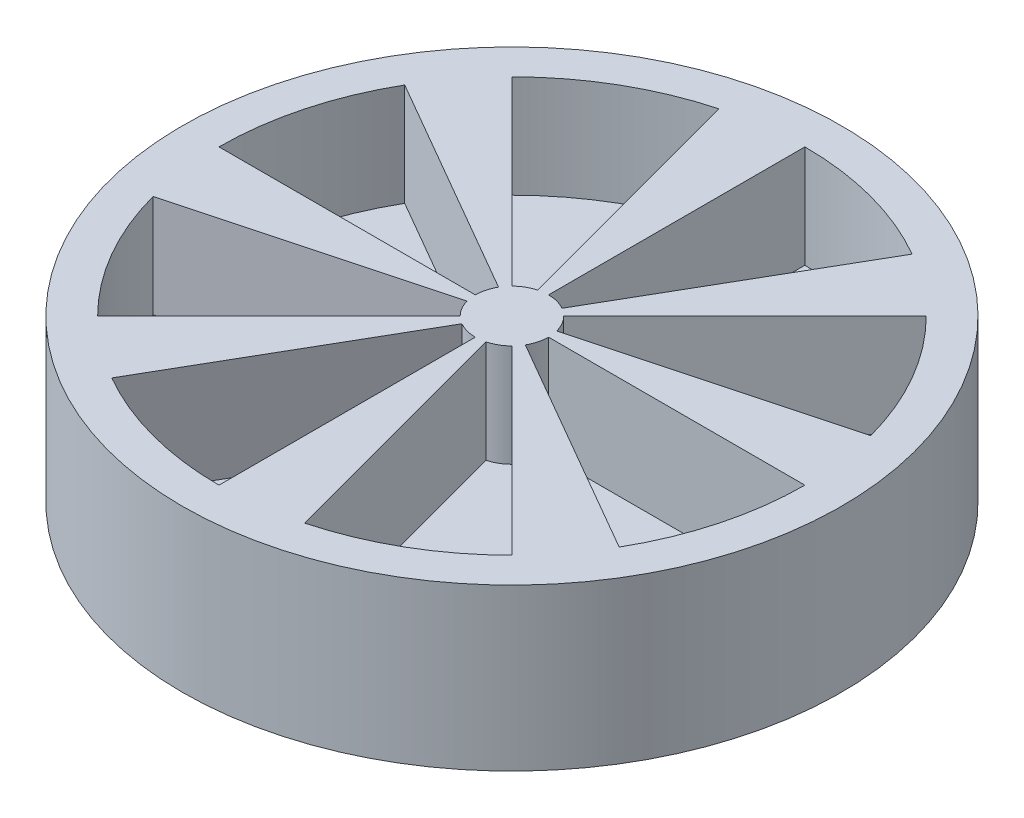
SolidWorks part; units mm, degrees
ref_plane "Front Plane" through (0, 0, 0) normal (0, 0, 1) x (1, 0, 0)
ref_plane "Top Plane" through (0, 0, 0) normal (0, 1, 0) x (1, 0, 0)
ref_plane "Right Plane" through (0, 0, 0) normal (1, 0, 0) x (0, 0, -1)
sketch "Sketch1" plane through (0, 0, 0) normal (0, 1, 0) x (1, 0, 0)
  circle A0 centre (0, 0) radius 22.5
  dimension "D1" = 45
extrude "Main Extrude for Plastic Mechansim Part" add sketch "Sketch1" along normal blind 11
sketch "Sketch2" plane through (0, 11, 0) normal (0, 1, 0) x (1, 0, 0)
  line L0 (0, 20) -> (0, 2.5)
  line L1 (-20, 0) -> (-2.5, 0)
  line L2 (-14.1421, -14.1421) -> (-1.7678, -1.7678)
  line L3 (-14.1421, 14.1421) -> (-1.7678, 1.7678)
  line L4 (-17.3205, 10) -> (-2.1651, 1.25)
  line L5 (-19.3185, 5.1764) -> (-2.4148, 0.647) construction
  line L6 (-19.3185, -5.1764) -> (-2.4148, -0.647)
  line L7 (-17.3205, -10) -> (-2.1651, -1.25) construction
  line L8 (10, 17.3205) -> (1.25, 2.1651)
  line L9 (5.1764, 19.3185) -> (0.647, 2.4148) construction
  line L10 (-5.1764, 19.3185) -> (-0.647, 2.4148)
  line L11 (-10, 17.3205) -> (-1.25, 2.1651) construction
  line L12 (0, -2.5) -> (0, -20)
  line L13 (-0.647, -2.4148) -> (-5.1764, -19.3185) construction
  line L14 (-1.25, -2.1651) -> (-10, -17.3205)
  line L15 (1.7678, 1.7678) -> (14.1421, 14.1421)
  line L16 (2.1651, 1.25) -> (17.3205, 10) construction
  line L17 (2.4148, 0.647) -> (19.3185, 5.1764)
  line L18 (2.5, 0) -> (20, 0)
  line L19 (2.4148, -0.647) -> (19.3185, -5.1764) construction
  line L20 (2.1651, -1.25) -> (17.3205, -10)
  line L21 (1.7678, -1.7678) -> (14.1421, -14.1421)
  line L22 (1.25, -2.1651) -> (10, -17.3205) construction
  line L23 (0.647, -2.4148) -> (5.1764, -19.3185)
  arc A0 (-5.1764, 19.3185) -> (-14.1421, 14.1421) centre (0, 0) ccw
  arc A1 (10, 17.3205) -> (0, 20) centre (0, 0) ccw
  arc A2 (19.3185, 5.1764) -> (14.1421, 14.1421) centre (0, 0) ccw
  arc A3 (17.3205, -10) -> (20, 0) centre (0, 0) ccw
  arc A4 (5.1764, -19.3185) -> (14.1421, -14.1421) centre (0, 0) ccw
  arc A5 (-10, -17.3205) -> (0, -20) centre (0, 0) ccw
  arc A6 (-19.3185, -5.1764) -> (-14.1421, -14.1421) centre (0, 0) ccw
  arc A7 (-17.3205, 10) -> (-20, 0) centre (0, 0) ccw
  arc A8 (-0.647, 2.4148) -> (-1.7678, 1.7678) centre (0, 0) ccw
  arc A9 (-2.1651, 1.25) -> (-2.5, 0) centre (0, 0) ccw
  arc A10 (-2.4148, -0.647) -> (-1.7678, -1.7678) centre (0, 0) ccw
  arc A11 (-1.25, -2.1651) -> (0, -2.5) centre (0, 0) ccw
  arc A12 (0.647, -2.4148) -> (1.7678, -1.7678) centre (0, 0) ccw
  arc A13 (2.1651, -1.25) -> (2.5, 0) centre (0, 0) ccw
  arc A14 (2.4148, 0.647) -> (1.7678, 1.7678) centre (0, 0) ccw
  arc A15 (1.25, 2.1651) -> (0, 2.5) centre (0, 0) ccw
  dimension "D1" = 40
  dimension "D6" = 5
  dimension "D2" = 45
  dimension "D3" = 45
  dimension "D4" = 15
  dimension "D5" = 15
extrude "Main Cut for Plastic Mechanism Part" cut sketch "Sketch2" against normal blind 7
